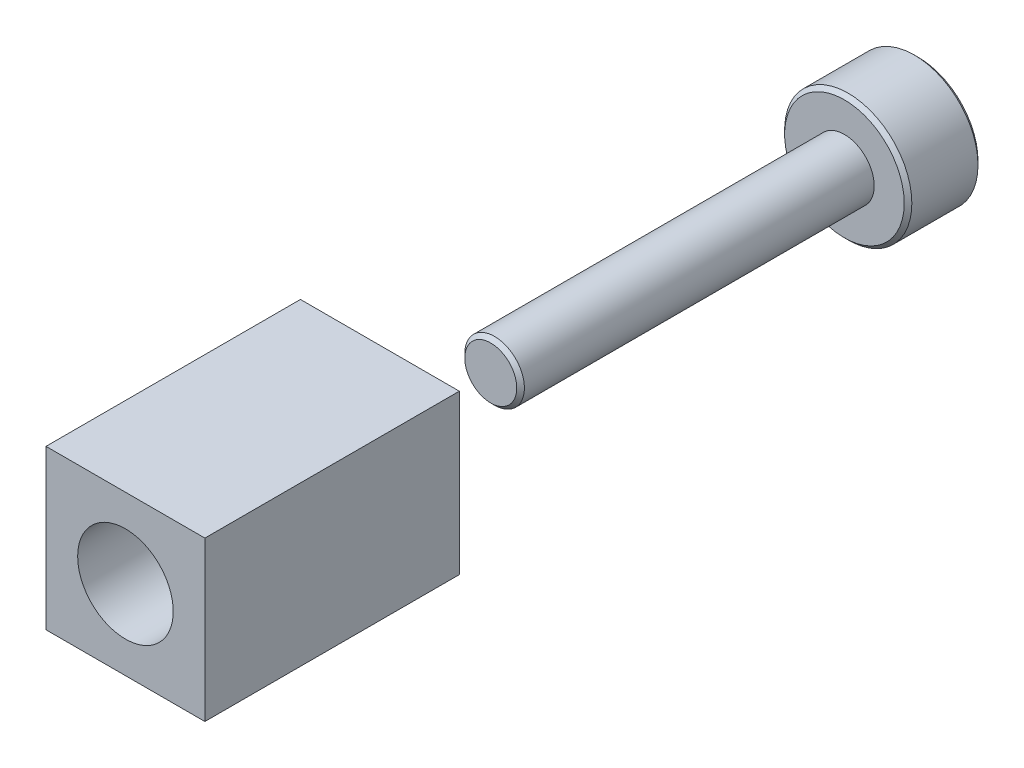
SolidWorks part; units mm, degrees
ref_plane "Front Plane" through (0, 0, 0) normal (0, 0, 1) x (1, 0, 0)
ref_plane "Top Plane" through (0, 0, 0) normal (0, 1, 0) x (1, 0, 0)
ref_plane "Right Plane" through (0, 0, 0) normal (1, 0, 0) x (0, 0, -1)
other "Configuration Table"
sketch "Sketch1" plane through (0, 0, 0) normal (0, 0, 1) x (1, 0, 0)
  circle A0 centre (0, 0) radius 12.7
  dimension "D1" = 25.4
extrude "Boss-Extrude1" add sketch "Sketch1" along normal blind 14.732
sketch "Sketch2" plane through (0, 0, 14.732) normal (0, 0, 1) x (1, 0, 0)
  circle A0 centre (0, 0) radius 5.9537
  dimension "D1" = 11.9074
extrude "Boss-Extrude2" add sketch "Sketch2" along normal blind 70.612
ref_plane "Plane1" through (0, 0, 107.4833) normal (0, 0, 1) x (1, 0, 0)
sketch "Sketch3" plane through (0, 0, 107.4833) normal (0, 0, 1) x (1, 0, 0)
  line L0 (15.8613, -15.8613) -> (-15.8613, 15.8613) construction
  line L1 (-15.8613, 15.8613) -> (15.8613, 15.8613)
  line L2 (-15.8613, 15.8613) -> (-15.8613, -15.8613)
  line L3 (-15.8613, -15.8613) -> (15.8613, -15.8613)
  line L4 (15.8613, 15.8613) -> (15.8613, -15.8613)
extrude "Boss-Extrude3" add sketch "Sketch3" along normal blind 50.8 separate body
sketch "Sketch4" plane through (0, 0, 107.4833) normal (0, 0, -1) x (-1, 0, 0)
  circle A0 centre (0, 0) radius 9.5417
  dimension "D1" = 19.0835
extrude "Cut-Extrude1" cut sketch "Sketch4" against normal through all
chamfer "Chamfer1" distance 0.762 angle 45 3 edges at (12.7, 0, 0) (12.7, 0, 14.732) (5.9537, 0, 85.344)
